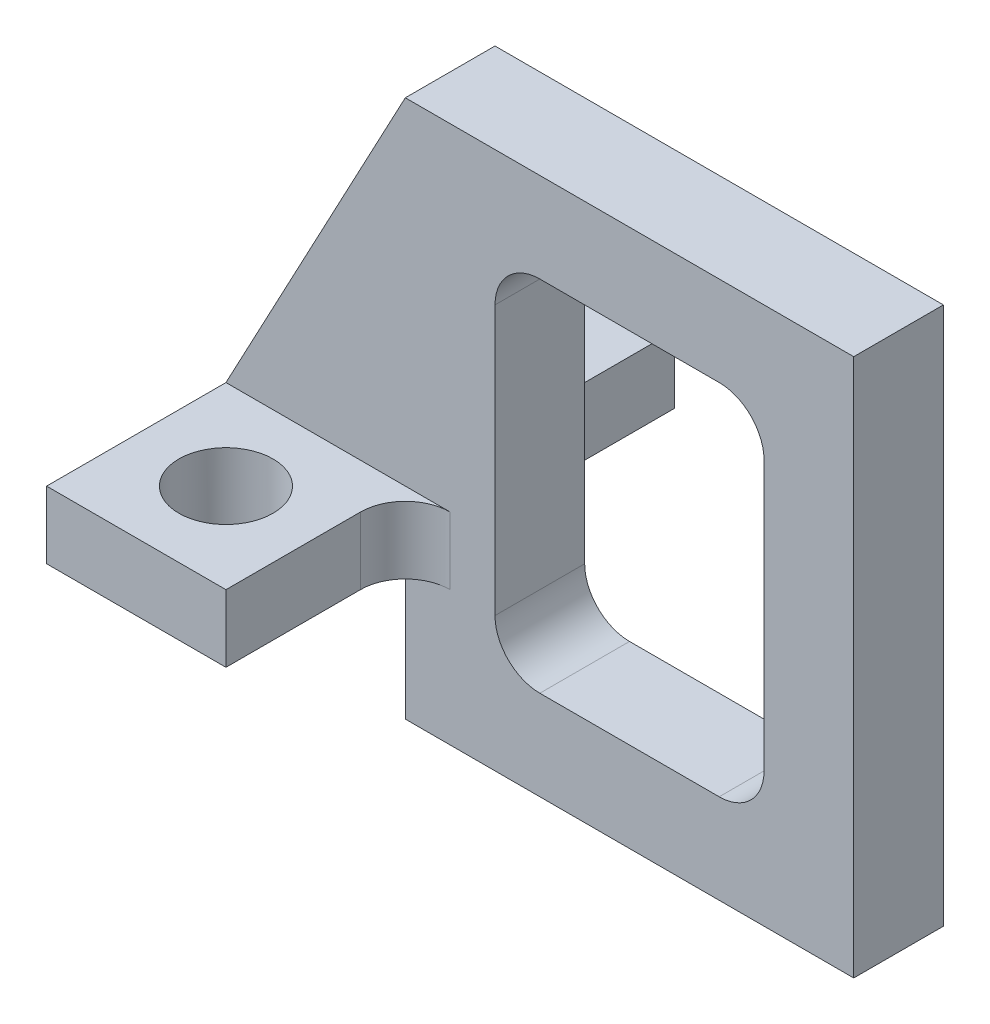
SolidWorks part; units mm, degrees
material "AISI 304"
ref_plane "Front" through (0, 0, 0) normal (0, 0, 1) x (1, 0, 0)
ref_plane "Top" through (0, 0, 0) normal (0, 1, 0) x (1, 0, 0)
ref_plane "Right" through (0, 0, 0) normal (1, 0, 0) x (0, 0, -1)
sketch "草图1" plane through (0, 0, 0) normal (0, 0, 1) x (1, 0, 0)
  line L0 (-4, -4) -> (-4, 20)
  line L1 (0, 0) -> (12, 0)
  line L2 (0, 0) -> (0, 16)
  line L3 (0, 16) -> (12, 16)
  line L4 (12, 0) -> (12, 16)
  line L5 (-4, 20) -> (16, 20)
  line L6 (16, -4) -> (16, 20)
  line L7 (-4, -4) -> (16, -4)
  dimension "D1" = 16
  dimension "D2" = 12
  dimension "D3" = 4
extrude "凸台-拉伸1" add sketch "草图1" along normal blind 4
sketch "草图2" plane through (-4, 0, 0) normal (-1, 0, 0) x (0, 0, 1)
  line L0 (2, 20) -> (2, 14.8722) construction
  line L1 (-8, 2) -> (12, 2)
  line L2 (-8, 2) -> (-8, 5)
  line L3 (-8, 5) -> (12, 5)
  line L4 (12, 2) -> (12, 5)
  line L5 (-8, 2) -> (12, 5) construction
  line L6 (-8, 5) -> (12, 2) construction
  line L7 (4, 20) -> (0, 20) construction
  line L8 (4, -4) -> (0, -4) construction
  point P0 (2, 3.5)
  dimension "D1" = 6
  dimension "D2" = 3
  dimension "D3" = 20
extrude "凸台-拉伸2" add sketch "草图2" along normal blind 8
sketch "草图3" plane through (0, 0, 4) normal (0, 0, 1) x (1, 0, 0)
  line L0 (-12, 5) -> (-4, 20)
  line L1 (-4, 20) -> (-4, 5)
  line L2 (-4, 5) -> (-12, 5)
extrude "凸台-拉伸3" add sketch "草图3" against normal blind 4
sketch "草图4" plane through (0, 5, 0) normal (0, 1, 0) x (1, 0, 0)
  line L0 (-4, 0) -> (-4, 8) construction
  line L1 (-12, 8) -> (-4, 8) construction
  line L2 (-12, -2) -> (-7.3751, -2) construction
  line L3 (-12, 0) -> (-12, -4) construction
  circle A0 centre (-8, 4) radius 2.1
  circle A1 centre (-8, -8) radius 2.1
  dimension "D3" = 4.2
  dimension "D1" = 4
  dimension "D2" = 4
extrude "切除-拉伸1" cut sketch "草图4" against normal through all
fillet "圆角1" radius 2 4 edges at (0, 16, 2) (12, 16, 2) (12, 0, 2) (0, 0, 2)
fillet "圆角4" radius 2 2 edges at (-4, 3.5, 4) (-4, 3.5, 0)
